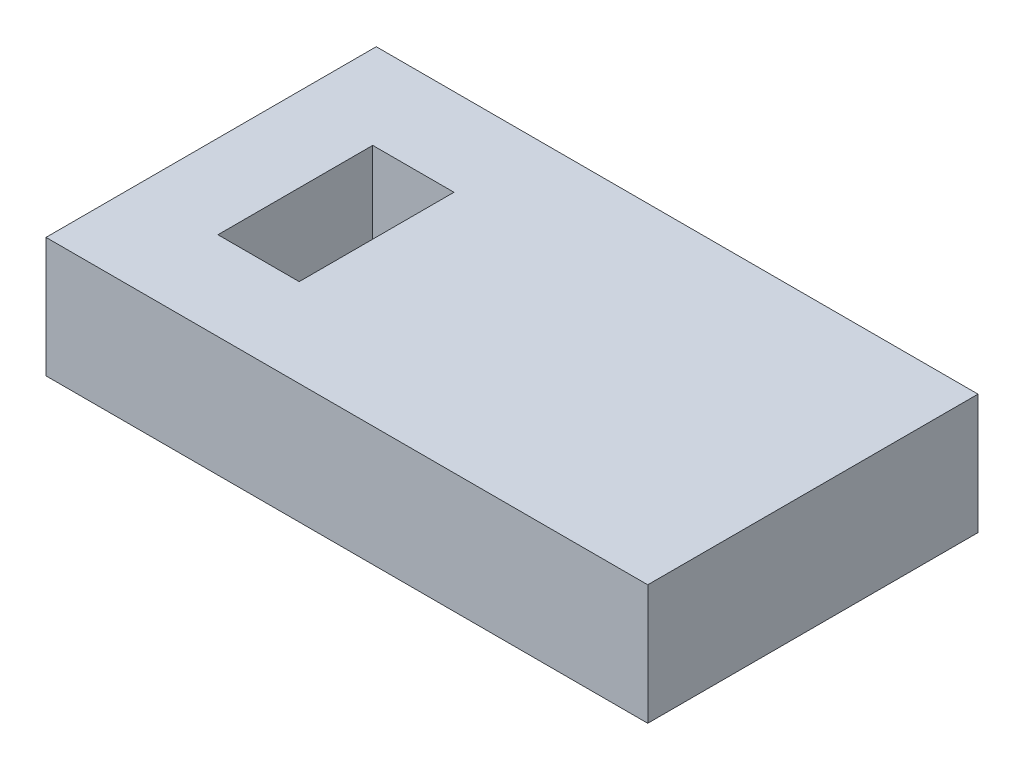
SolidWorks part; units mm, degrees
ref_plane "Front Plane" through (0, 0, 0) normal (0, 0, 1) x (1, 0, 0)
ref_plane "Top Plane" through (0, 0, 0) normal (0, 1, 0) x (1, 0, 0)
ref_plane "Right Plane" through (0, 0, 0) normal (1, 0, 0) x (0, 0, -1)
sketch "Sketch1" plane through (0, 0, 0) normal (0, 1, 0) x (1, 0, 0)
  line L1 (0, 0) -> (155.5087, 0)
  line L2 (0, 0) -> (0, 85.3434)
  line L3 (0, 85.3434) -> (155.5087, 85.3434)
  line L4 (155.5087, 0) -> (155.5087, 85.3434)
  line L5 (21.6264, 22.8085) -> (42.6264, 22.8085)
  line L6 (21.6264, 22.8085) -> (21.6264, 62.8085)
  line L7 (21.6264, 62.8085) -> (42.6264, 62.8085)
  line L8 (42.6264, 22.8085) -> (42.6264, 62.8085)
  dimension "D1" = 21
  dimension "D2" = 40
extrude "Boss-Extrude1" add sketch "Sketch1" along normal blind 30
sketch "Sketch2" plane through (0, 0, 0) normal (0, -1, 0) x (1, 0, 0)
  line L1 (0, 0) -> (155.5087, 0)
  line L2 (0, 0) -> (0, -85.3434)
  line L3 (0, -85.3434) -> (155.5087, -85.3434)
  line L4 (155.5087, 0) -> (155.5087, -85.3434)
extrude "Boss-Extrude2" add sketch "Sketch2" along normal blind 1
